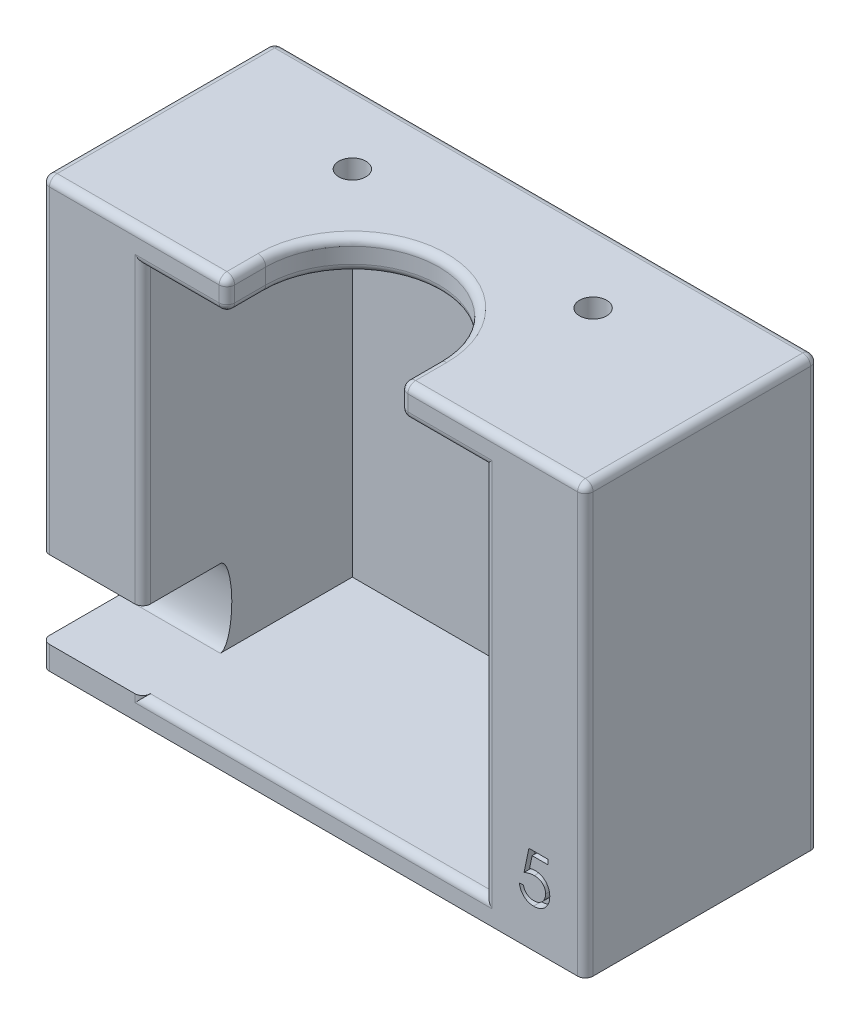
SolidWorks part; units mm, degrees
ref_plane "Alzado" through (0, 0, 0) normal (0, 0, 1) x (1, 0, 0)
ref_plane "Planta" through (0, 0, 0) normal (0, 1, 0) x (1, 0, 0)
ref_plane "Vista lateral" through (0, 0, 0) normal (1, 0, 0) x (0, 0, -1)
sketch "Croquis1" plane through (0, 0, 0) normal (0, 1, 0) x (1, 0, 0)
  line L1 (-35, -15) -> (35, -15)
  line L2 (-35, -15) -> (-35, 15)
  line L3 (-35, 15) -> (35, 15)
  line L4 (35, -15) -> (35, 15)
  line L5 (-35, -15) -> (35, 15) construction
  line L6 (-35, 15) -> (35, -15) construction
  point P0 (0, 0)
extrude "Saliente-Extruir1" add sketch "Croquis1" along normal blind 55
sketch "Croquis5" plane through (0, 0, 15) normal (0, 0, 1) x (1, 0, 0)
  line L0 (0, 0) -> (0, 3) construction
  line L1 (0, 3) -> (-22, 3) construction
  line L2 (-22, 3) -> (-22, 51) construction
  line L3 (-22, 51) -> (22, 51) construction
  line L4 (22, 51) -> (22, 3) construction
  line L6 (-22, 51) -> (22, 51)
  line L7 (-22, 51) -> (-22, 3)
  line L8 (-22, 3) -> (22, 3)
  line L9 (22, 51) -> (22, 3)
extrude "Cortar-Extruir3" cut sketch "Croquis5" against normal blind 27
sketch "Croquis6" plane through (0, 51, 0) normal (0, -1, 0) x (1, 0, 0)
  line L0 (0, -12) -> (0, 10) construction
  line L1 (22, -12) -> (-22, -12) construction
  circle A0 centre (0, 10) radius 11.15
extrude "Cortar-Extruir4" cut sketch "Croquis6" against normal up to next
sketch "Croquis7" plane through (0, 55, 0) normal (0, 1, 0) x (1, 0, 0)
  line L0 (-11.15, -10) -> (-11.15, -15) construction
  line L1 (-35, -15) -> (-9.9661, -15) construction
  line L2 (-11.15, -15) -> (11.15, -15) construction
  line L3 (9.9661, -15) -> (35, -15) construction
  line L4 (11.15, -15) -> (11.15, -10) construction
  line L5 (11.15, -10) -> (-11.15, -10) construction
  line L7 (-11.15, -10) -> (11.15, -10)
  line L8 (-11.15, -10) -> (-11.15, -15)
  line L9 (-11.15, -15) -> (11.15, -15)
  line L10 (11.15, -10) -> (11.15, -15)
  arc A0 (9.9661, -15) -> (-9.9661, -15) centre (0, -10) ccw construction
extrude "Cortar-Extruir5" cut sketch "Croquis7" against normal up to next
sketch "Croquis9" plane through (0, 0, -15) normal (0, 0, -1) x (-1, 0, 0)
  line L0 (0, 0) -> (0, 32) construction
  line L1 (-35, 0) -> (35, 0) construction
  line L2 (0, 32) -> (-27.5, 32) construction
  line L3 (0, 32) -> (27.5, 32) construction
  circle A0 centre (-27.5, 32) radius 4.15
  circle A1 centre (27.5, 32) radius 4.15
extrude "Cortar-Extruir6" cut sketch "Croquis9" against normal blind 27
fillet "Redondeo1" radius 1 22 edges at (11.15, 55, 12.5) (16.575, 51, 15) (11.15, 51, 12.5) (0, 51, -1.15) (-11.15, 51, 12.5) (-16.575, 51, 15) (0, 55, -1.15) (-11.15, 55, 12.5) (-23.075, 55, 15) (23.075, 55, 15) (35, 55, 0) (35, 27.5, -15) (0, 3, 15) (-22, 27, 15) (22, 27, 15) (35, 27.5, 15) (-35, 27.5, 15) (-35, 27.5, -15) (0, 55, -15) (-35, 55, 0) (-11.15, 53, 15) (11.15, 53, 15)
sketch "Croquis10" plane through (0, 0, 15) normal (0, 0, 1) x (1, 0, 0)
  line L3 (23, 5.1282) -> (34, 5.1282) construction
  line L4 (23, 52) -> (23, 2) construction
  line L5 (34, 0) -> (34, 54) construction
  text T1 "5" font "Century Gothic" height 6
extrude "Cortar-Extruir7" cut sketch "Croquis10" against normal blind 1
sketch "Croquis11" plane through (0, 55, 0) normal (0, 1, 0) x (1, 0, 0)
  line L0 (0, -10) -> (-15.5, -10) construction
  line L1 (-15.5, -10) -> (-15.5, 5.5) construction
  line L2 (-15.5, 5.5) -> (15.5, 5.5) construction
  circle A0 centre (-15.5, 5.5) radius 1.75
  circle A1 centre (15.5, 5.5) radius 1.75
  dimension "D3" = 3.5
  dimension "D4" = 3.5
  dimension "D1" = 15.5
  dimension "D2" = 31
extrude "Cortar-Extruir8" cut sketch "Croquis11" against normal up to next
sketch "Croquis14" plane through (-22, 0, 0) normal (1, 0, 0) x (0, 0, -1)
  line L0 (-15, 2) -> (-15, 52) construction
  line L1 (-15, 3) -> (-5, 3)
  line L2 (-15, 3) -> (-15, 13)
  line L3 (-15, 13) -> (-5, 13)
  line L5 (12, 3) -> (-14, 3) construction
  ellipse E0 centre (-5, 8) end of major axis (-5, 13) minor radius 1.4807 (-5, 3) -> (-5, 13) ccw
  dimension "D1" = 10
  dimension "D2" = 10
  dimension "D3" = 0
  dimension "D4" = 0
extrude "Cortar-Extruir9" cut sketch "Croquis14" against normal up to next
